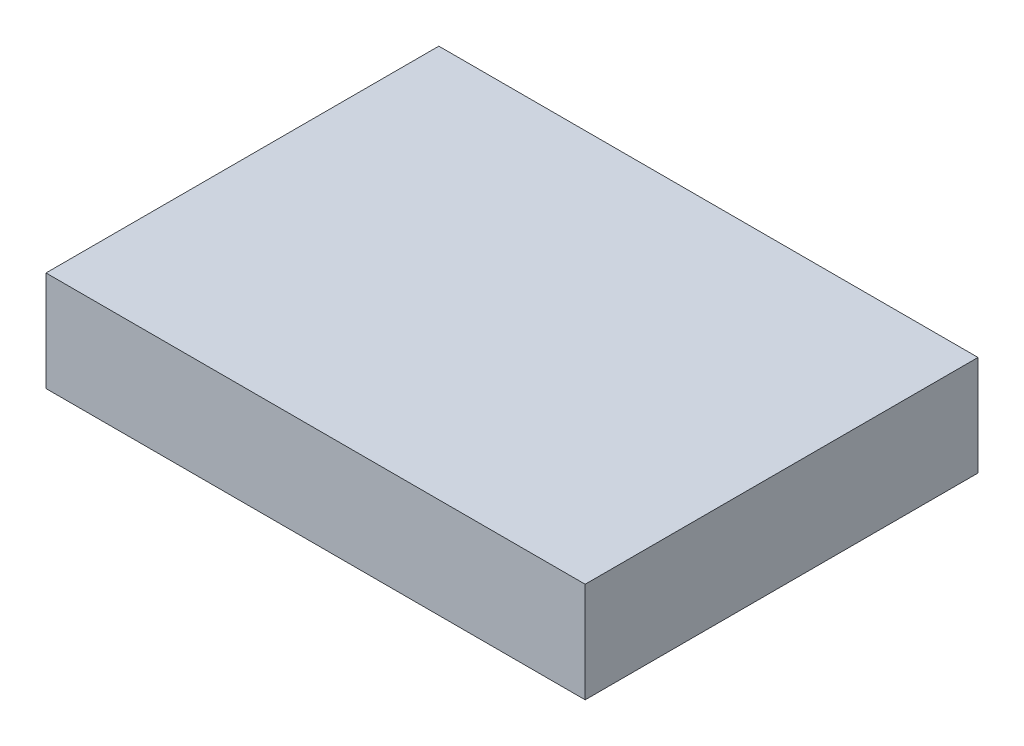
SolidWorks part; units mm, degrees
ref_plane "Front Plane" through (0, 0, 0) normal (0, 0, 1) x (1, 0, 0)
ref_plane "Top Plane" through (0, 0, 0) normal (0, 1, 0) x (1, 0, 0)
ref_plane "Right Plane" through (0, 0, 0) normal (1, 0, 0) x (0, 0, -1)
sketch "Sketch1" plane through (0, 0, 0) normal (0, 1, 0) x (1, 0, 0)
  line L1 (0, 0) -> (35, 0)
  line L2 (0, 0) -> (0, 25.5)
  line L3 (0, 25.5) -> (35, 25.5)
  line L4 (35, 0) -> (35, 25.5)
  dimension "D1" = 35
  dimension "D2" = 25.5
extrude "Boss-Extrude1" add sketch "Sketch1" along normal blind 6.5
